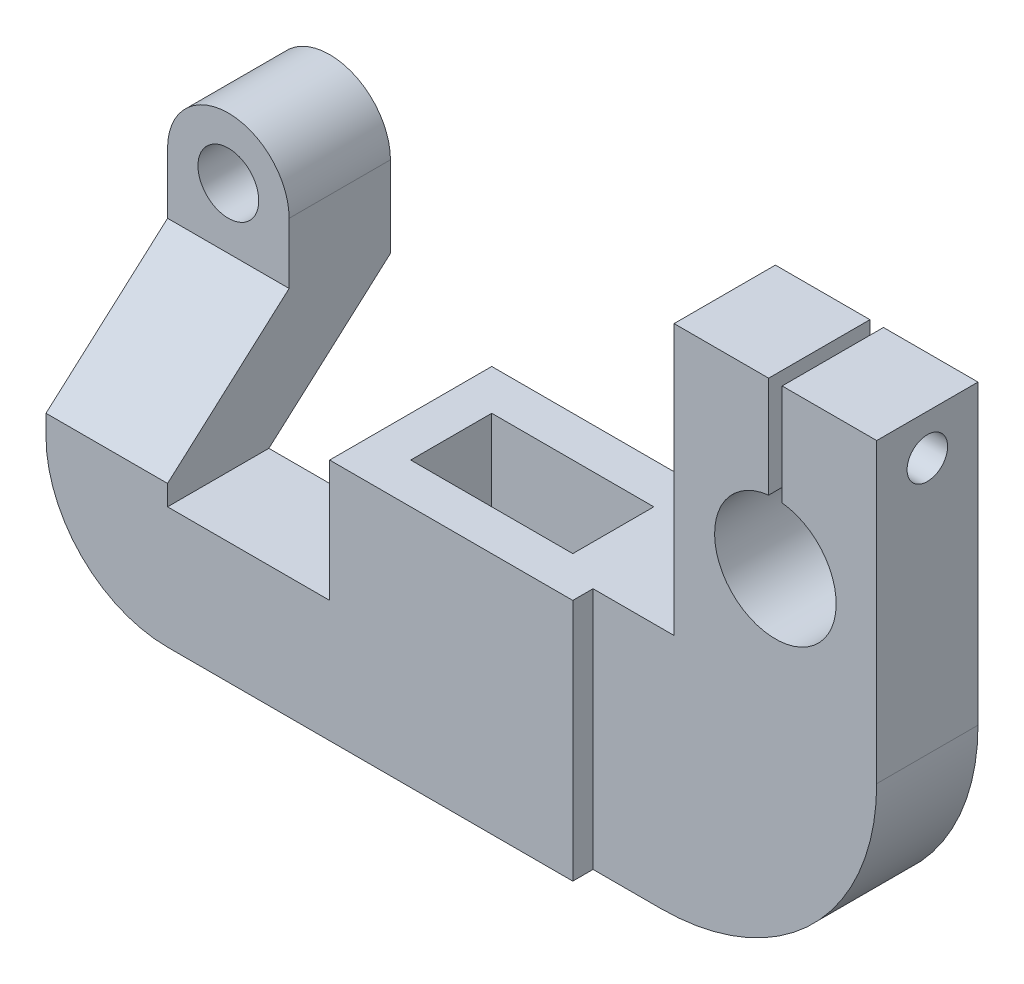
SolidWorks part; units mm, degrees
ref_plane "前视基准面" through (0, 0, 0) normal (0, 0, 1) x (1, 0, 0)
ref_plane "上视基准面" through (0, 0, 0) normal (0, 1, 0) x (1, 0, 0)
ref_plane "右视基准面" through (0, 0, 0) normal (1, 0, 0) x (0, 0, -1)
other "Configuration Table"
sketch "草图1" plane through (0, 0, 0) normal (0, 0, 1) x (1, 0, 0)
  line L0 (52.8288, 42.3249) -> (52.8288, 27.3249)
  line L2 (-53.1712, 12.3249) -> (-53.1712, -15.6751)
  line L3 (-35.1712, -33.6751) -> (34.8288, -33.6751)
  line L4 (66.8288, 42.3249) -> (66.8288, -1.6751)
  line L5 (-41.5385, 20.9313) -> (66.8288, -33.6751) construction
  line L6 (-53.1712, -33.6751) -> (66.8288, 42.3249) construction
  line L8 (50.8288, 27.3249) -> (50.8288, 42.3249)
  line L9 (52.8288, 42.3249) -> (66.8288, 42.3249)
  line L10 (50.8288, 27.3249) -> (52.8288, 27.3249) construction
  line L11 (36.8288, 42.3249) -> (36.8288, 2.3249)
  line L12 (36.8288, 2.3249) -> (-11.1712, 2.3249)
  line L13 (-11.1712, 2.3249) -> (-11.1712, -15.6751)
  line L14 (-11.1712, -15.6751) -> (-35.1712, -15.6751)
  line L15 (-35.1712, -15.6751) -> (-35.1712, 12.3249)
  line L16 (36.8288, 42.3249) -> (50.8288, 42.3249)
  arc A0 (34.8288, -33.6751) -> (66.8288, -1.6751) centre (34.8288, -1.6751) ccw
  arc A1 (-53.1712, -15.6751) -> (-35.1712, -33.6751) centre (-35.1712, -15.6751) ccw
  arc A2 (50.8288, 27.3249) -> (52.8288, 27.3249) centre (51.8288, 18.3807) ccw
  arc A3 (-35.1712, 12.3249) -> (-53.1712, 12.3249) centre (-44.1712, 12.3249) ccw
  circle A4 centre (-44.1712, 12.3249) radius 4.5
  point P0 (0, 0)
  point P17 (51.8288, 27.3249)
  dimension "D3" = 32
  dimension "D4" = 18
  dimension "D8" = 9
  dimension "D16" = 9
  dimension "D1" = 120
  dimension "D2" = 76
  dimension "D5" = 14
  dimension "D6" = 15
  dimension "D7" = 2
  dimension "D9" = 14
  dimension "D10" = 36
  dimension "D11" = 18
  dimension "D12" = 18
  dimension "D13" = 24
  dimension "D14" = 28
  dimension "D15" = 66.8288
extrude "凸台-拉伸2" add sketch "草图1" along normal blind 33
sketch "草图4" plane through (-53.1712, 0, 0) normal (-1, 0, 0) x (0, 0, 1)
  line L0 (0, 12.3249) -> (0, 0.3249) construction
  line L1 (18, -15.6751) -> (33, -15.6751) construction
  line L2 (33, -15.6751) -> (0, -15.6751) construction
  line L3 (0, 0.3249) -> (18, -15.6751)
  line L4 (15, 21.3249) -> (15, 3.3249)
  line L6 (33, 12.3249) -> (33, -15.6751) construction
  line L7 (18, -15.6751) -> (18, -33.6751)
  line L8 (33, -33.6751) -> (0, -33.6751) construction
  line L9 (18, -33.6751) -> (0, -33.6751)
  line L10 (0, 0.3249) -> (0, -33.6751)
  line L12 (33, 21.3249) -> (0, 21.3249) construction
  line L13 (15, 21.3249) -> (33, 21.3249)
  line L15 (33, 12.3249) -> (0, 12.3249) construction
  line L16 (15, 3.3249) -> (33, -12.6751)
  line L17 (33, 21.3249) -> (33, -12.6751)
  dimension "D1" = 12
  dimension "D2" = 15
  dimension "D3" = 9
  dimension "D4" = 15
extrude "切除-拉伸3" cut sketch "草图4" against normal blind 42
sketch "草图6" plane through (0, 2.3249, 0) normal (0, 1, 0) x (1, 0, 0)
  line L0 (-11.1712, -33) -> (-11.1712, -18) construction
  line L1 (18.8288, -15) -> (-5.1712, -15)
  line L2 (18.8288, -15) -> (18.8288, -27)
  line L3 (18.8288, -27) -> (-5.1712, -27)
  line L4 (-5.1712, -15) -> (-5.1712, -27)
  line L5 (6.8288, -27) -> (6.8288, -15) construction
  line L6 (18.8288, -21) -> (-5.1712, -21) construction
  line L7 (36.8288, -33) -> (-11.1712, -33) construction
  point P0 (6.8288, -21)
  dimension "D1" = 6
  dimension "D2" = 6
  dimension "D3" = 12
  dimension "D4" = 24
extrude "切除-拉伸4" cut sketch "草图6" against normal through all
sketch "草图7" plane through (0, 2.3249, 0) normal (0, 1, 0) x (1, 0, 0)
  line L0 (66.8288, -33) -> (66.8288, 0) construction
  line L1 (-11.1712, 0) -> (66.8288, 0)
  line L2 (-11.1712, 0) -> (-11.1712, -9)
  line L3 (-11.1712, -9) -> (66.8288, -9)
  line L4 (66.8288, 0) -> (66.8288, -9)
  line L5 (18.8288, -15) -> (-5.1712, -15) construction
  dimension "D1" = 6
extrude "切除-拉伸5" cut sketch "草图7" against normal through all both and the other way through all
sketch "草图8" plane through (0, 2.3249, 0) normal (0, 1, 0) x (1, 0, 0)
  line L0 (36.8288, -9) -> (-11.1712, -9) construction
  line L1 (24.8288, -9) -> (66.8288, -9)
  line L2 (24.8288, -9) -> (24.8288, -15)
  line L3 (24.8288, -15) -> (66.8288, -15)
  line L4 (66.8288, -9) -> (66.8288, -15)
  line L5 (66.8288, -33) -> (66.8288, -9) construction
  line L6 (36.8288, -33) -> (-11.1712, -33) construction
  line L7 (24.8288, -33) -> (66.8288, -33)
  line L8 (24.8288, -33) -> (24.8288, -30)
  line L9 (24.8288, -30) -> (66.8288, -30)
  line L10 (66.8288, -33) -> (66.8288, -30)
  line L11 (18.8288, -27) -> (18.8288, -15) construction
  point P16 (24.8288, -12.6122)
  dimension "D1" = 6
  dimension "D2" = 6
  dimension "D3" = 15
  dimension "D4" = 6
extrude "切除-拉伸6" cut sketch "草图8" against normal through all both and the other way through all contours L2 L1 L4 L3 | L8 L7 L10 L9
sketch "草图9" plane through (36.8288, 0, 0) normal (-1, 0, 0) x (0, 0, 1)
  line L0 (15, 36.3249) -> (30, 36.3249) construction
  line L1 (30, 42.3249) -> (30, 2.3249) construction
  line L2 (30, 42.3249) -> (15, 42.3249) construction
  line L3 (15, 42.3249) -> (15, 2.3249) construction
  circle A0 centre (22.5, 36.3249) radius 3
  point P4 (0, 0)
  point P9 (22.5, 36.3249)
  dimension "D1" = 6
  dimension "D2" = 6
extrude "切除-拉伸7" cut sketch "草图9" against normal through all both
